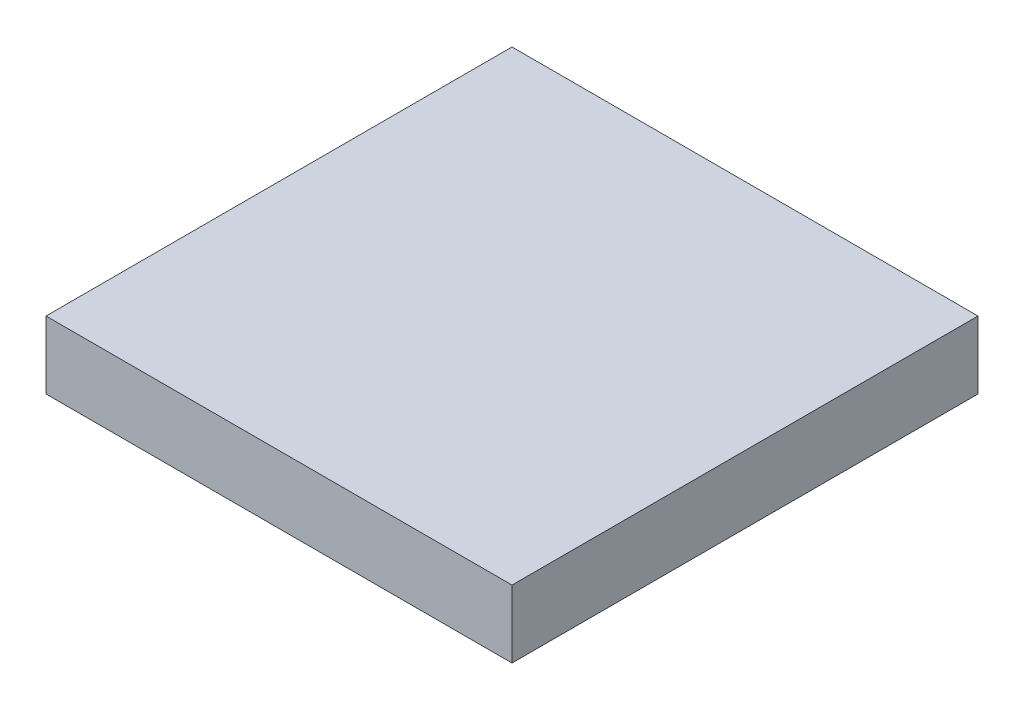
SolidWorks part; units mm, degrees
ref_plane "Front Plane" through (0, 0, 0) normal (0, 0, 1) x (1, 0, 0)
ref_plane "Top Plane" through (0, 0, 0) normal (0, 1, 0) x (1, 0, 0)
ref_plane "Right Plane" through (0, 0, 0) normal (1, 0, 0) x (0, 0, -1)
sketch "Sketch1" plane through (0, 0, 0) normal (0, 1, 0) x (1, 0, 0)
  line L1 (0, 0) -> (35.052, 0)
  line L2 (0, 0) -> (0, 35.052)
  line L3 (0, 35.052) -> (35.052, 35.052)
  line L4 (35.052, 0) -> (35.052, 35.052)
  dimension "D1" = 35.052
  dimension "D2" = 35.052
extrude "Boss-Extrude1" add sketch "Sketch1" along normal blind 5.08 contours L1 L4 L3 L2
equation "\"ph_length\"=1.38"
equation "\"D1@Sketch1\"=\"ph_length\""
equation "\"ph_height\"=0.2"
equation "\"D1@Boss-Extrude1\"=\"ph_height\""
